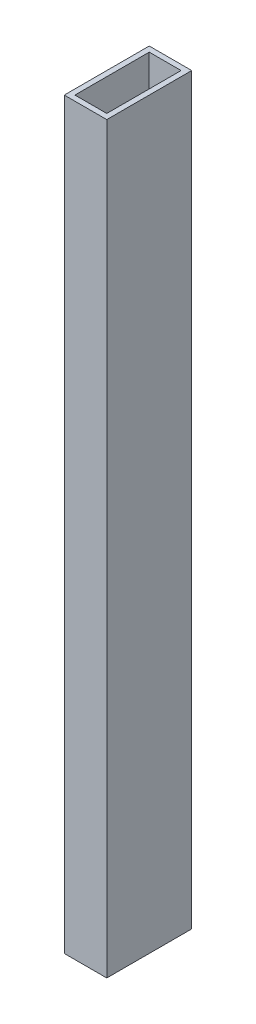
SolidWorks part; units mm, degrees
ref_plane "Front Plane" through (0, 0, 0) normal (0, 0, 1) x (1, 0, 0)
ref_plane "Top Plane" through (0, 0, 0) normal (0, 1, 0) x (1, 0, 0)
ref_plane "Right Plane" through (0, 0, 0) normal (1, 0, 0) x (0, 0, -1)
sketch "Sketch1" plane through (0, 0, 0) normal (0, 1, 0) x (1, 0, 0)
  line L0 (-9.525, 22.225) -> (9.525, 22.225)
  line L1 (-12.7, -25.4) -> (12.7, -25.4)
  line L2 (-12.7, -25.4) -> (-12.7, 25.4)
  line L3 (-12.7, 25.4) -> (12.7, 25.4)
  line L4 (12.7, -25.4) -> (12.7, 25.4)
  line L5 (-12.7, -25.4) -> (12.7, 25.4) construction
  line L6 (-12.7, 25.4) -> (12.7, -25.4) construction
  line L7 (9.525, -22.225) -> (9.525, 22.225)
  line L8 (-9.525, -22.225) -> (9.525, -22.225)
  line L9 (-9.525, -22.225) -> (-9.525, 22.225)
  point P0 (0, 0)
  dimension "D1" = 25.4
  dimension "D2" = 50.8
  dimension "D3" = 3.175
extrude "Boss-Extrude1" add sketch "Sketch1" along normal blind 444.5
